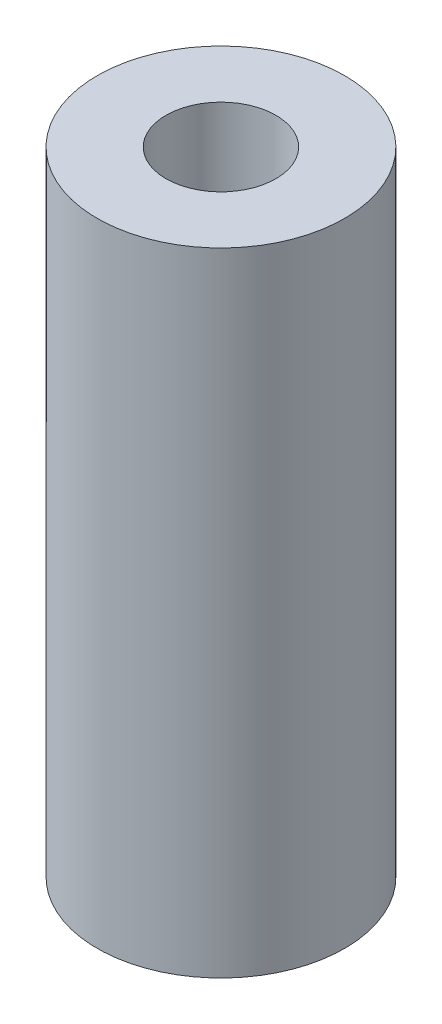
SolidWorks part; units mm, degrees
ref_plane "Plan de face" through (0, 0, 0) normal (0, 0, 1) x (1, 0, 0)
ref_plane "Plan de dessus" through (0, 0, 0) normal (0, 1, 0) x (1, 0, 0)
ref_plane "Plan de droite" through (0, 0, 0) normal (1, 0, 0) x (0, 0, -1)
sketch "Esquisse1" plane through (0, 0, 0) normal (0, 1, 0) x (1, 0, 0)
  circle A0 centre (0, 0) radius 9
extrude "Boss.-Extru.1" add sketch "Esquisse1" along normal blind 23
sketch "Esquisse2" plane through (0, 0, 0) normal (0, -1, 0) x (-1, 0, 0)
  circle A0 centre (0, 0) radius 4.5
  circle A1 centre (0, 0) radius 9
extrude "Enlèv. mat.-Extru.2" cut sketch "Esquisse2" against normal through all
sketch "Esquisse3" plane through (0, 0, 0) normal (0, -1, 0) x (-1, 0, 0)
  circle A0 centre (0, 0) radius 1.5
extrude "Enlèv. mat.-Extru.3" cut sketch "Esquisse3" against normal blind 5
sketch "Esquisse4" plane through (0, 23, 0) normal (0, 1, 0) x (1, 0, 0)
  circle A0 centre (0, 0) radius 2
extrude "Enlèv. mat.-Extru.4" cut sketch "Esquisse4" against normal blind 5
